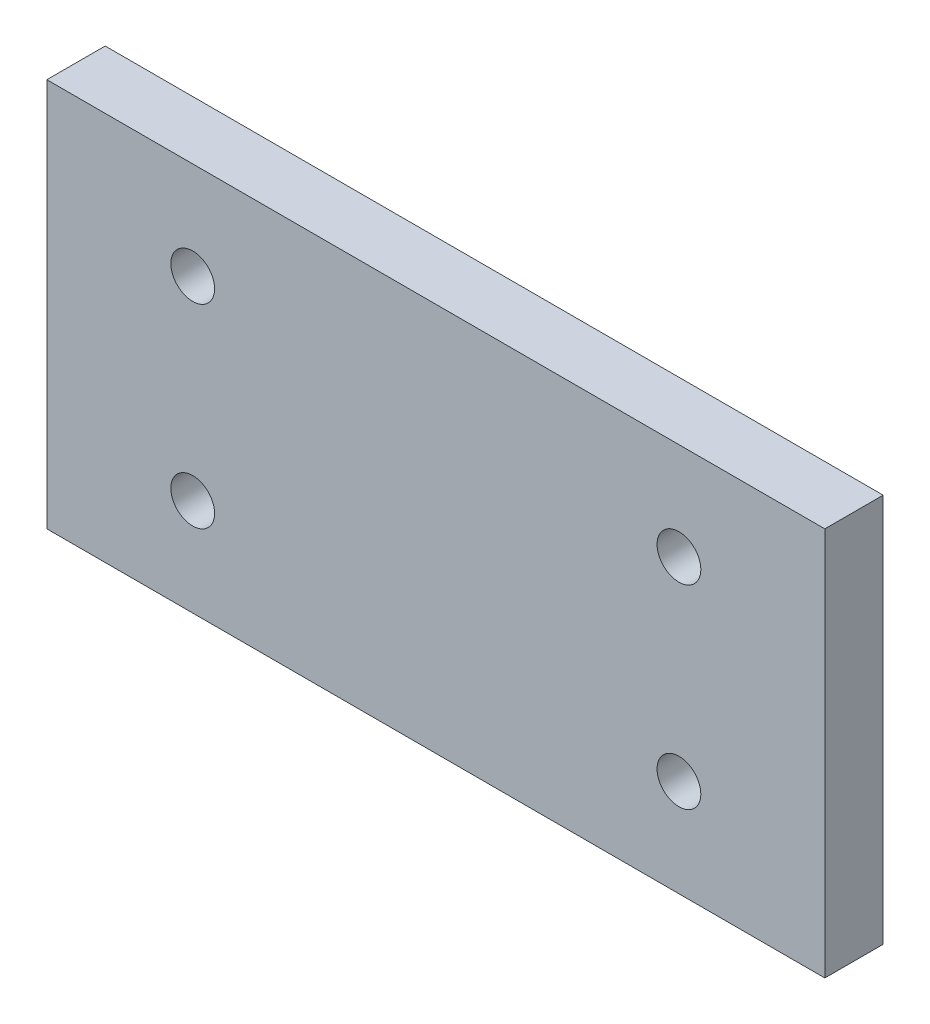
SolidWorks part; units mm, degrees
ref_plane "前视基准面" through (0, 0, 0) normal (0, 0, 1) x (1, 0, 0)
ref_plane "上视基准面" through (0, 0, 0) normal (0, 1, 0) x (1, 0, 0)
ref_plane "右视基准面" through (0, 0, 0) normal (1, 0, 0) x (0, 0, -1)
other "Configuration Table"
sketch "草图1" plane through (0, 0, 0) normal (0, 0, 1) x (1, 0, 0)
  line L1 (-40, -20) -> (40, -20)
  line L2 (-40, -20) -> (-40, 20)
  line L3 (-40, 20) -> (40, 20)
  line L4 (40, -20) -> (40, 20)
extrude "双面拼接板" add sketch "草图1" along normal blind 6
sketch "草图2" plane through (0, 0, 0) normal (0, 0, 1) x (1, 0, 0)
  circle A0 centre (-25, -10) radius 2.25
  circle A1 centre (-25, 10) radius 2.25
  circle A2 centre (25, -10) radius 2.25
  circle A3 centre (25, 10) radius 2.25
extrude "拼接M4孔" cut sketch "草图2" against normal through all and the other way through all
